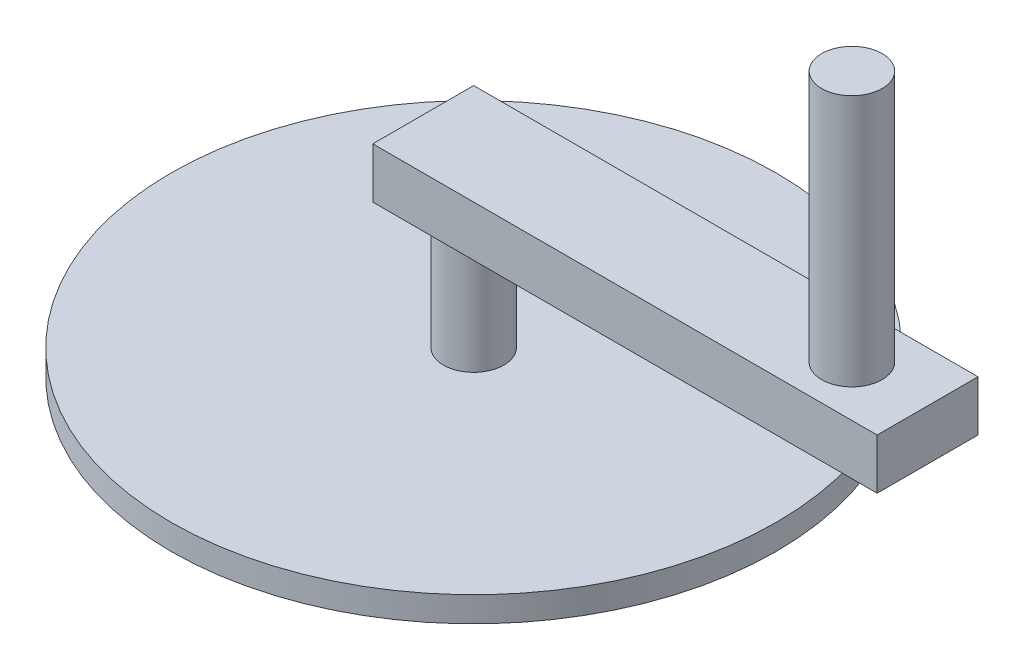
SolidWorks part; units mm, degrees
ref_plane "正面" through (0, 0, 0) normal (0, 0, 1) x (1, 0, 0)
ref_plane "平面" through (0, 0, 0) normal (0, 1, 0) x (1, 0, 0)
ref_plane "右側面" through (0, 0, 0) normal (1, 0, 0) x (0, 0, -1)
sketch "ｽｹｯﾁ1" plane through (0, 0, 0) normal (0, 1, 0) x (1, 0, 0)
  line L1 (-100, 20) -> (0, 20)
  line L2 (-100, 20) -> (-100, 0)
  line L3 (-100, 0) -> (0, 0)
  line L4 (0, 20) -> (0, 0)
  dimension "D1" = 20
  dimension "D2" = 100
extrude "ﾎﾞｽ - 押し出し1" add sketch "ｽｹｯﾁ1" along normal blind 10
sketch "ｽｹｯﾁ4" plane through (0, 10, 0) normal (0, 1, 0) x (1, 0, 0)
  circle A0 centre (-15, 10) radius 6
extrude "ﾎﾞｽ - 押し出し2" add sketch "ｽｹｯﾁ4" along normal blind 50
sketch "ｽｹｯﾁ6" plane through (0, 0, 0) normal (0, -1, 0) x (1, 0, 0)
  circle A0 centre (-90, -10) radius 6
extrude "ﾎﾞｽ - 押し出し3" add sketch "ｽｹｯﾁ6" along normal blind 30
sketch "ｽｹｯﾁ7" plane through (0, -30, 0) normal (0, -1, 0) x (1, 0, 0)
  circle A0 centre (-90, -10) radius 30
  dimension "D1" = 60
extrude "ﾎﾞｽ - 押し出し4" add sketch "ｽｹｯﾁ7" along normal blind 5
sketch "ｽｹｯﾁ8" plane through (0, -30, 0) normal (0, 1, 0) x (1, 0, 0)
  circle A0 centre (-90, 10) radius 60
  dimension "D1" = 120
extrude "ﾎﾞｽ - 押し出し5" add sketch "ｽｹｯﾁ8" along normal blind 5
